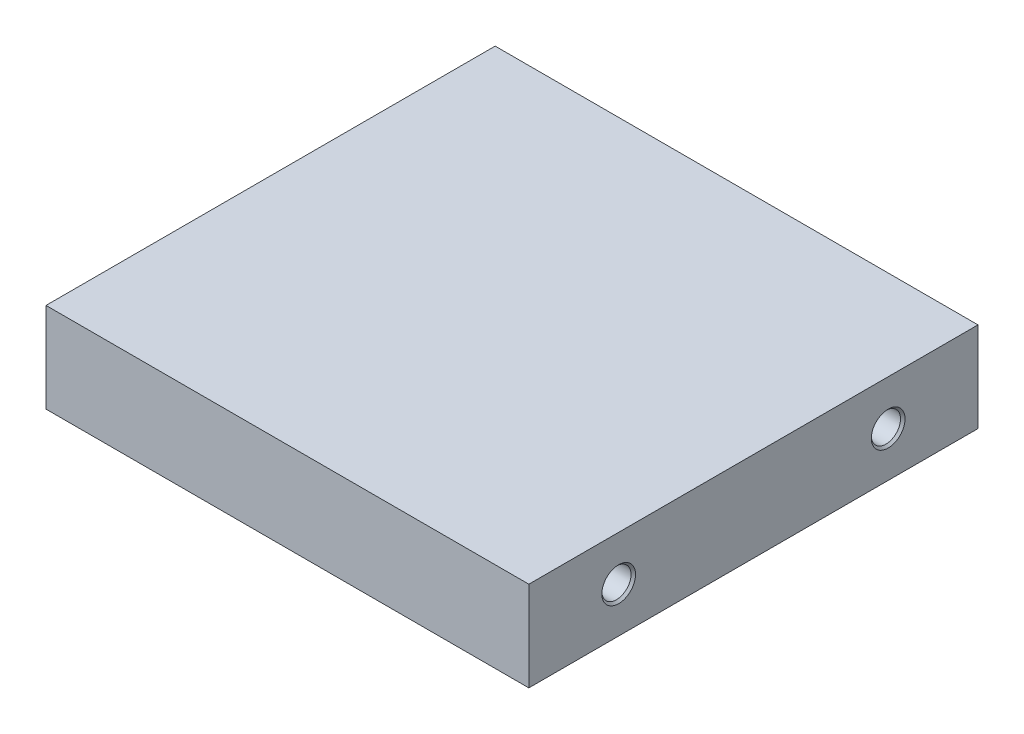
SolidWorks part; units mm, degrees
ref_plane "前基準面" through (0, 0, 0) normal (0, 0, 1) x (1, 0, 0)
ref_plane "上基準面" through (0, 0, 0) normal (0, 1, 0) x (1, 0, 0)
ref_plane "右基準面" through (0, 0, 0) normal (1, 0, 0) x (0, 0, -1)
sketch "草圖1" plane through (0, 0, 0) normal (0, 1, 0) x (1, 0, 0)
  line L1 (-21.5, 20) -> (21.5, 20)
  line L2 (-21.5, 20) -> (-21.5, -20)
  line L3 (-21.5, -20) -> (21.5, -20)
  line L4 (21.5, 20) -> (21.5, -20)
  line L5 (-21.5, 20) -> (21.5, -20) construction
  line L6 (-21.5, -20) -> (21.5, 20) construction
  point P0 (0, 0)
  dimension "D1" = 43
  dimension "D2" = 40
extrude "填料-伸長1" add sketch "草圖1" along normal blind 8
sketch "草圖2" plane through (-21.5, 0, 0) normal (-1, 0, 0) x (0, 0, 1)
  line L0 (-20, 0) -> (20, 0) construction
  line L1 (-20, 8) -> (-20, 0) construction
  line L2 (20, 8) -> (20, 0) construction
  circle A0 centre (-12, 4) radius 1.3
  circle A1 centre (12, 4) radius 1.3
  dimension "D1" = 2.6
  dimension "D2" = 4
  dimension "D3" = 8
  dimension "D4" = 8
extrude "除料-伸長1" cut sketch "草圖2" against normal blind 8
mirror "鏡射1" about plane through (0, 0, 0) normal (1, 0, 0) of "除料-伸長1"
chamfer "導角1" distance 0.2 4 edges at (-21.5, 4, -10.7) (-21.5, 4, 13.3) (21.5, 4, 13.3) (21.5, 4, -10.7)
